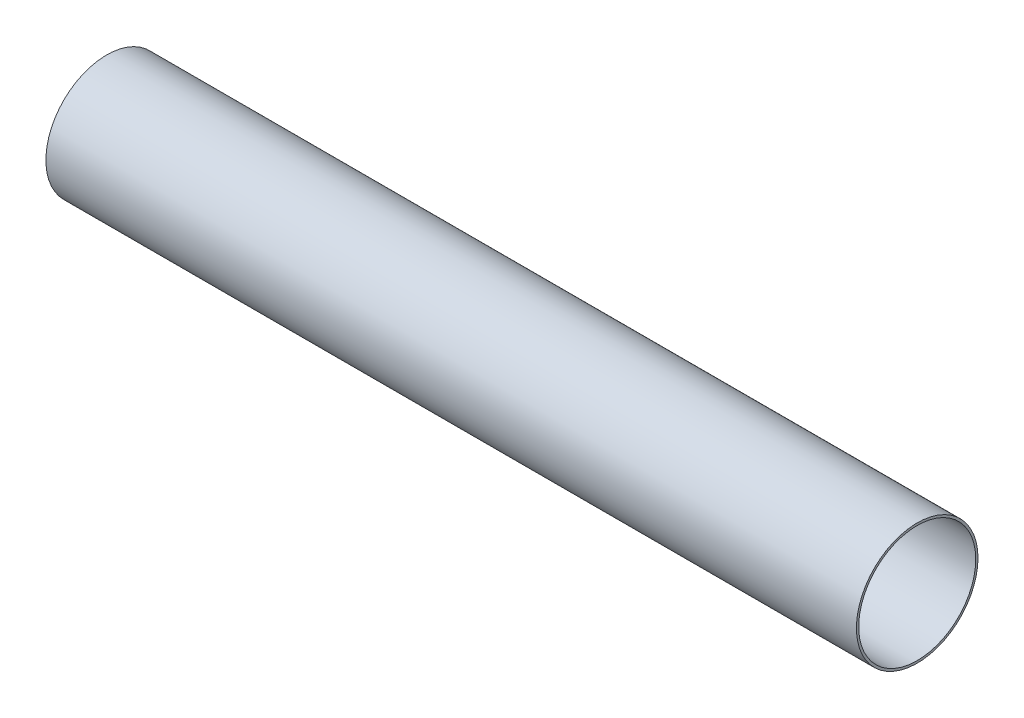
SolidWorks part; units mm, degrees
ref_plane "Front" through (0, 0, 0) normal (0, 0, 1) x (1, 0, 0)
ref_plane "Top" through (0, 0, 0) normal (0, 1, 0) x (1, 0, 0)
ref_plane "Right" through (0, 0, 0) normal (1, 0, 0) x (0, 0, -1)
sketch "Sketch1" plane through (0, 0, 0) normal (1, 0, 0) x (0, 0, -1)
  line L0 (18.3388, 0) -> (19.05, 0) construction
  line L1 (18.3388, 0) -> (19.05, 0) construction
  line L2 (18.6944, 0) -> (18.6944, 1.0672) construction
  circle A0 centre (0, 0) radius 19.05
  circle A1 centre (0, 0) radius 18.3388
  point P4 (19.05, 0)
  point P5 (18.3388, 0)
  dimension "OD" = 38.1
  dimension "ID" = 36.6776
  dimension "Wall Thickness" = 0.7112
sketch "Sketch2" plane through (0, 0, 0) normal (0, 0, 1) x (1, 0, 0)
  line L0 (-127, 0) -> (127, 0) construction
  point P2 (-79.375, 0)
  point P3 (79.375, 0)
  dimension "D1" = 47.625
  dimension "D2" = 47.625
sketch "Sketch3" plane through (0, 0, 0) normal (1, 0, 0) x (0, 0, -1)
  circle A0 centre (0, 0) radius 18.3388 construction
  circle A1 centre (0, 0) radius 19.05 construction
  circle A2 centre (0, 0) radius 18.3388
  circle A3 centre (0, 0) radius 19.05
extrude "Boss-Extrude1" add sketch "Sketch3" along normal mid plane 254
sketch "Sketch4" plane through (0, 0, 0) normal (0, 0, 1) x (1, 0, 0)
  line L0 (-127, 19.05) -> (-127, -19.05) construction
  line L1 (-127, 19.05) -> (-127, -19.05)
  dimension "D1" = 38.1
equation "\"D1@Boss-Extrude1\"=\"Length@Sketch2\""
equation "\"D1@Sketch2\"=\"OD@Sketch1\"*1.25"
equation "\"D2@Sketch2\"=\"D1@Sketch2\""
